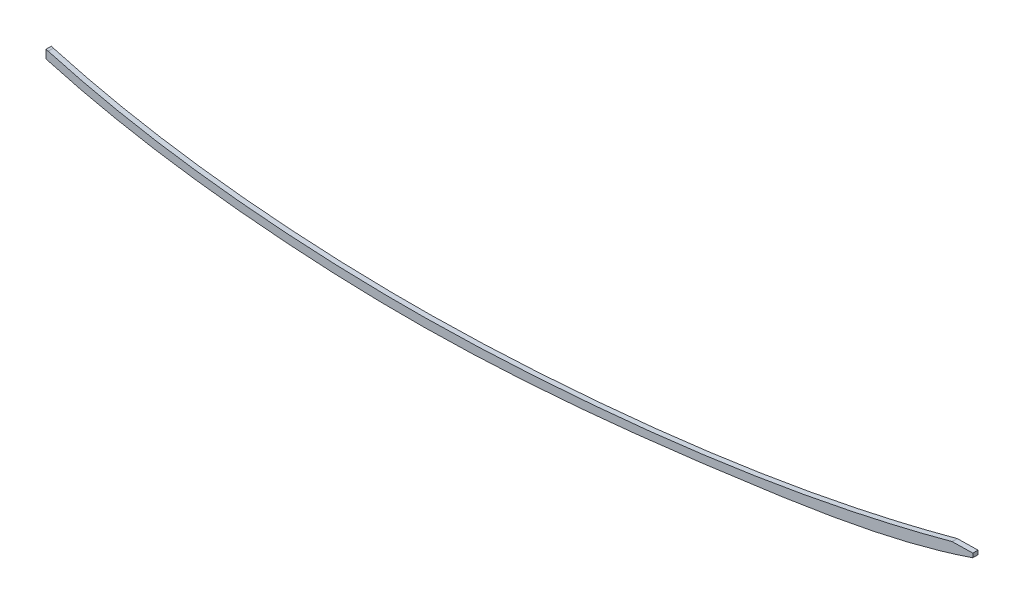
SolidWorks part; units mm, degrees
ref_plane "Front Plane" through (0, 0, 0) normal (0, 0, 1) x (1, 0, 0)
ref_plane "Top Plane" through (0, 0, 0) normal (0, 1, 0) x (1, 0, 0)
ref_plane "Right Plane" through (0, 0, 0) normal (1, 0, 0) x (0, 0, -1)
sketch "Sketch1" plane through (0, 0, 0) normal (0, 0, 1) x (1, 0, 0)
  line L0 (339.7439, -1.9709) -> (327.0287, -2.2074)
  line L8 (100, 152.9548) -> (100, -45.3184) construction
  line L9 (200, 248.6206) -> (200, -33.7603) construction
  line L10 (0, 117.4834) -> (0, -50.4184) construction
  line L11 (-100, 123.1215) -> (-100, -46.2526) construction
  line L12 (-200, 120.0606) -> (-200, -31.3689) construction
  line L13 (-230, 120.7597) -> (-230, -23.7765) construction
  line L14 (-228.6381, -18.9655) -> (-230, -18.58)
  line L15 (-230, -18.58) -> (-230, -23.7765)
  line L21 (339.7439, -1.9709) -> (339.7439, -4.4784)
  spline S0 degree 3 poles (-230, -23.7765) (-187.6249, -35.8108) (-110.7573, -47.3077) (0.0074, -52.0922) (100.3447, -46.3618) (200.2092, -34.2197) (281.1655, -22.0174) (326.582, -8.9534) (339.7439, -4.4784) knots 0 0 0 0 0.225071 0.39564 0.566277 0.737859 0.910959 0.981894 0.981894 0.981894 0.981894
  spline S2 degree 3 poles (-228.6381, -18.9655) (-205.328, -25.5641) (-169.7138, -33.0483) (-121.5067, -39.3797) (-73.0123, -43.7076) (-12.2033, -45.8684) (48.6364, -44.0362) (97.2557, -40.6615) (145.7964, -36.203) (206.1927, -28.4414) (266.0139, -17.2756) (306.1232, -7.7432) (322.4722, -3.4401) (327.0287, -2.2074) knots 0 0 0 0 0.125 0.1875 0.25 0.375 0.5 0.5625 0.625 0.75 0.875 0.9375 0.961706 0.961706 0.961706 0.961706
extrude "Boss-Extrude1" add sketch "Sketch1" along normal blind 3.2 contours S2 L0 L21 S0 L15 L14
